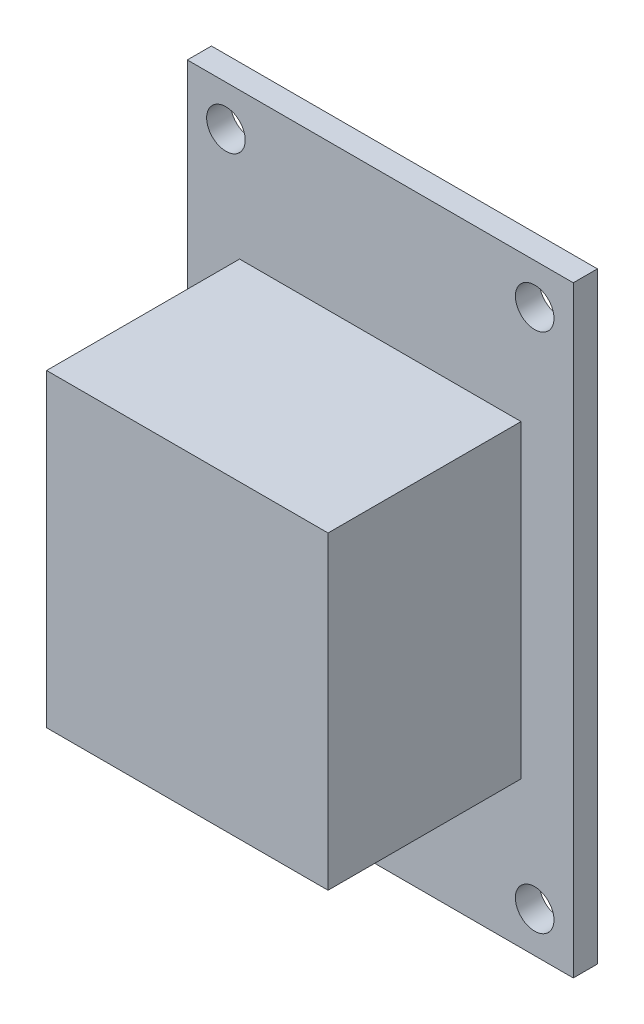
SolidWorks part; units mm, degrees
ref_plane "Front Plane" through (0, 0, 0) normal (0, 0, 1) x (1, 0, 0)
ref_plane "Top Plane" through (0, 0, 0) normal (0, 1, 0) x (1, 0, 0)
ref_plane "Right Plane" through (0, 0, 0) normal (1, 0, 0) x (0, 0, -1)
sketch "Sketch1" plane through (0, 0, 0) normal (0, 0, 1) x (1, 0, 0)
  line L1 (-12.7, 19.812) -> (12.7, 19.812)
  line L2 (-12.7, 19.812) -> (-12.7, -19.812)
  line L3 (-12.7, -19.812) -> (12.7, -19.812)
  line L4 (12.7, 19.812) -> (12.7, -19.812)
  line L5 (-12.7, 19.812) -> (12.7, -19.812) construction
  line L6 (-12.7, -19.812) -> (12.7, 19.812) construction
  point P0 (0, 0)
  dimension "D1" = 25.4
  dimension "D2" = 39.624
extrude "Boss-Extrude1" add sketch "Sketch1" along normal blind 1.5875
sketch "Sketch2" plane through (0, 0, 1.5875) normal (0, 0, 1) x (1, 0, 0)
  line L1 (-9.2613, 10.1821) -> (9.2613, 10.1821)
  line L2 (-9.2613, 10.1821) -> (-9.2613, -10.1821)
  line L3 (-9.2613, -10.1821) -> (9.2613, -10.1821)
  line L4 (9.2613, 10.1821) -> (9.2613, -10.1821)
  line L5 (-9.2613, 10.1821) -> (9.2613, -10.1821) construction
  line L6 (-9.2613, -10.1821) -> (9.2613, 10.1821) construction
  point P0 (0, 0)
extrude "Boss-Extrude2" add sketch "Sketch2" along normal blind 12.7
sketch "Sketch3" plane through (0, 0, 1.5875) normal (0, 0, 1) x (1, 0, 0)
  line L1 (10.16, -17.145) -> (-10.16, -17.145) construction
  line L2 (10.16, -17.145) -> (10.16, 17.145) construction
  line L3 (10.16, 17.145) -> (-10.16, 17.145) construction
  line L4 (-10.16, -17.145) -> (-10.16, 17.145) construction
  line L5 (10.16, -17.145) -> (-10.16, 17.145) construction
  line L6 (10.16, 17.145) -> (-10.16, -17.145) construction
  circle A0 centre (-10.16, 17.145) radius 1.27
  circle A1 centre (10.16, 17.145) radius 1.27
  circle A2 centre (10.16, -17.145) radius 1.27
  circle A3 centre (-10.16, -17.145) radius 1.27
  point P0 (0, 0)
  dimension "D3" = 2.54
  dimension "D1" = 34.29
  dimension "D2" = 20.32
extrude "Cut-Extrude1" cut sketch "Sketch3" against normal through all
